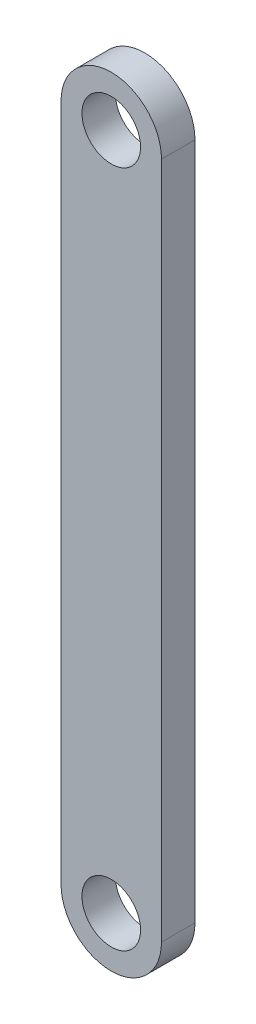
SolidWorks part; units mm, degrees
ref_plane "Front Plane" through (0, 0, 0) normal (0, 0, 1) x (1, 0, 0)
ref_plane "Top Plane" through (0, 0, 0) normal (0, 1, 0) x (1, 0, 0)
ref_plane "Right Plane" through (0, 0, 0) normal (1, 0, 0) x (0, 0, -1)
sketch "Sketch1" plane through (0, 0, 0) normal (0, 0, 1) x (1, 0, 0)
  line L0 (0, 0) -> (514.35, 0) construction
  line L1 (0, 0) -> (0, 257.175) construction
  line L2 (0, 0) -> (0, 257.175) construction
  line L3 (-19.05, 0) -> (-19.05, 257.175)
  line L4 (19.05, 0) -> (19.05, 257.175)
  arc A0 (-19.05, 0) -> (19.05, 0) centre (0, 0) ccw
  arc A1 (19.05, 257.175) -> (-19.05, 257.175) centre (0, 257.175) ccw
  circle A2 centre (0, 257.175) radius 11.1125
  circle A3 centre (0, 0) radius 11.1125
  point P3 (0, 128.5875)
  dimension "D3" = 19.05
  dimension "D4" = 22.225
  dimension "D5" = 22.225
  dimension "D1" = 514.35
  dimension "D2" = 257.175
extrude "Boss-Extrude1" add sketch "Sketch1" along normal blind 12.7
